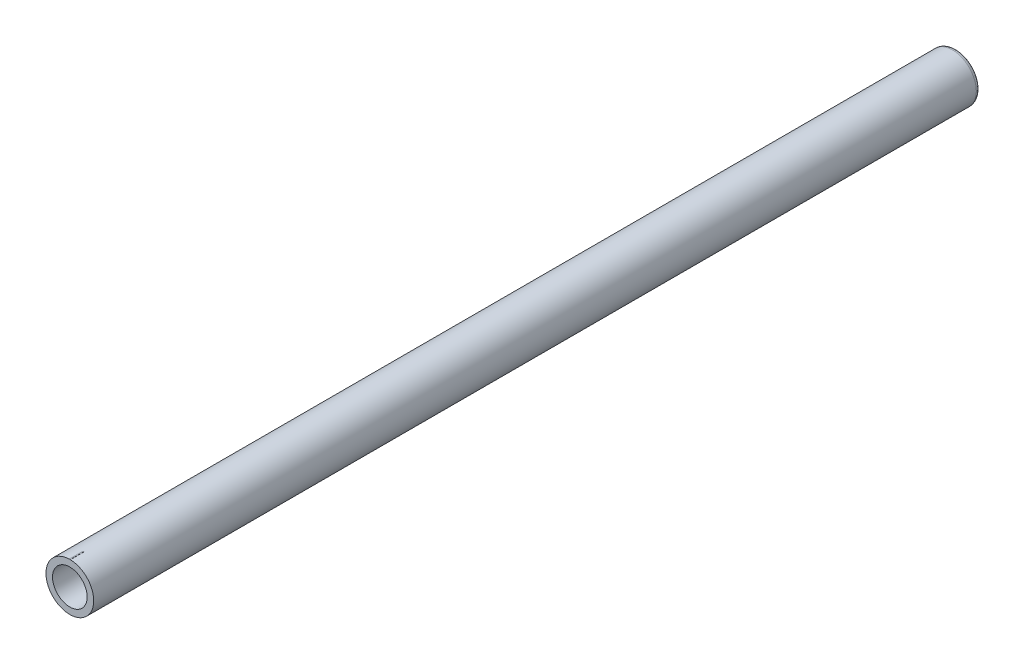
SolidWorks part; units mm, degrees
ref_plane "Alzado" through (0, 0, 0) normal (0, 0, 1) x (1, 0, 0)
ref_plane "Planta" through (0, 0, 0) normal (0, 1, 0) x (1, 0, 0)
ref_plane "Vista lateral" through (0, 0, 0) normal (1, 0, 0) x (0, 0, -1)
sketch "Croquis2" plane through (0, 0, 0) normal (0, 0, 1) x (1, 0, 0)
  circle A0 centre (0, 0) radius 17.5
  dimension "D1" = 35
extrude "Saliente-Extruir1" add sketch "Croquis2" against normal blind 650
sketch "Croquis3" plane through (0, 0, 0) normal (0, 0, 1) x (1, 0, 0)
  circle A0 centre (0, 0) radius 12.7
  dimension "D1" = 25.4
extrude "Cortar-Extruir1" cut sketch "Croquis3" against normal blind 640
fillet "Redondeo1" radius 3 1 edges at (17.5, 0, -650)
sketch "Croquis4" plane through (0, 0, 0) normal (0, 0, 1) x (1, 0, 0)
  line L1 (-0.3674, 17.5943) -> (0.3674, 17.5943)
  line L2 (-0.3674, 17.5943) -> (-0.3674, 17.4057)
  line L3 (-0.3674, 17.4057) -> (0.3674, 17.4057)
  line L4 (0.3674, 17.5943) -> (0.3674, 17.4057)
  line L5 (-0.3674, 17.5943) -> (0.3674, 17.4057) construction
  line L6 (-0.3674, 17.4057) -> (0.3674, 17.5943) construction
  circle A0 centre (0, 0) radius 17.5 construction
  point P0 (0, 17.5)
extrude "Saliente-Extruir2" add sketch "Croquis4" against normal blind 10
